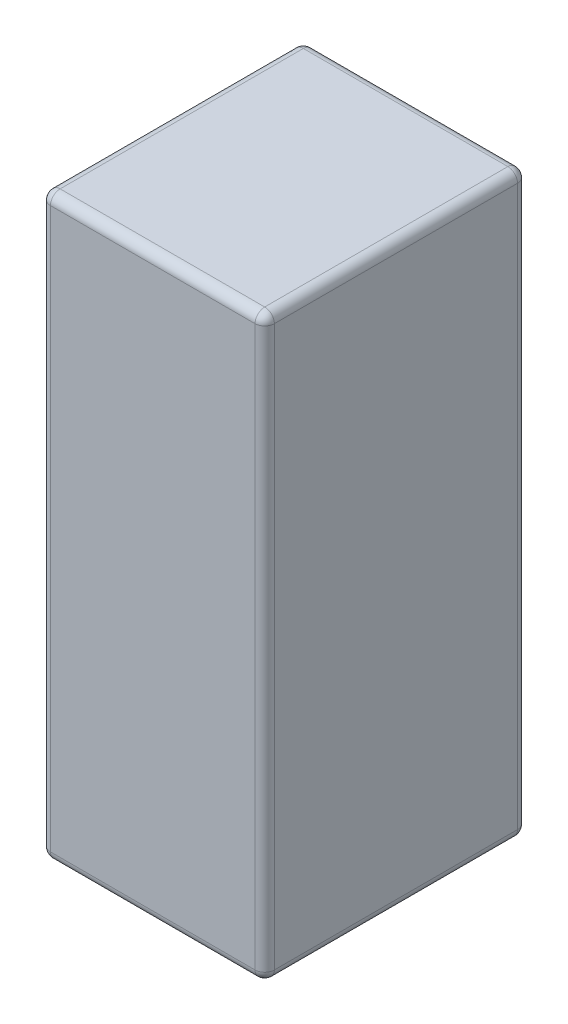
SolidWorks part; units mm, degrees
ref_plane "Front Plane" through (0, 0, 0) normal (0, 0, 1) x (1, 0, 0)
ref_plane "Top Plane" through (0, 0, 0) normal (0, 1, 0) x (1, 0, 0)
ref_plane "Right Plane" through (0, 0, 0) normal (1, 0, 0) x (0, 0, -1)
sketch "Sketch2" plane through (0, 0, 0) normal (0, 1, 0) x (1, 0, 0)
  line L1 (-14.5, 17) -> (14.5, 17)
  line L2 (-14.5, 17) -> (-14.5, -17)
  line L3 (-14.5, -17) -> (14.5, -17)
  line L4 (14.5, 17) -> (14.5, -17)
  line L5 (-14.5, 17) -> (14.5, -17) construction
  line L6 (-14.5, -17) -> (14.5, 17) construction
  point P0 (0, 0)
  dimension "D1" = 29
  dimension "D2" = 34
extrude "Boss-Extrude1" add sketch "Sketch2" along normal blind 75
fillet "Fillet1" radius 1.25 12 edges at (0, 0, -17) (-14.5, 0, 0) (0, 0, 17) (14.5, 0, 0) (-14.5, 37.5, -17) (14.5, 37.5, -17) (-14.5, 37.5, 17) (14.5, 37.5, 17) (0, 75, 17) (-14.5, 75, 0) (0, 75, -17) (14.5, 75, 0)
